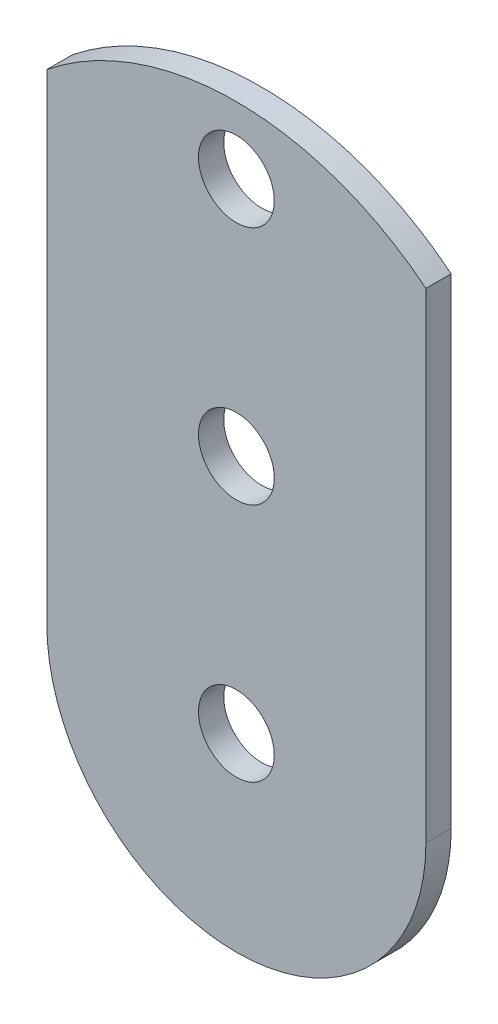
SolidWorks part; units mm, degrees
ref_plane "前视基准面" through (0, 0, 0) normal (0, 0, 1) x (1, 0, 0)
ref_plane "上视基准面" through (0, 0, 0) normal (0, 1, 0) x (1, 0, 0)
ref_plane "右视基准面" through (0, 0, 0) normal (1, 0, 0) x (0, 0, -1)
sketch "草图1" plane through (0, 0, 0) normal (0, 0, 1) x (1, 0, 0)
  line L0 (14.742, -3.0551) -> (14.742, -41.0551)
  line L1 (-15.258, -3.0551) -> (-15.258, -41.0551)
  circle A0 centre (-0.258, -3.0551) radius 3
  circle A1 centre (-0.258, -22.0551) radius 3
  circle A2 centre (-0.258, -41.0551) radius 3
  arc A3 (-15.258, -41.0551) -> (14.742, -41.0551) centre (-0.258, -41.0551) ccw
  arc A5 (14.742, -3.0551) -> (-15.258, -3.0551) centre (-0.258, -21.6236) ccw
extrude "凸台-拉伸1" add sketch "草图1" along normal blind 2
